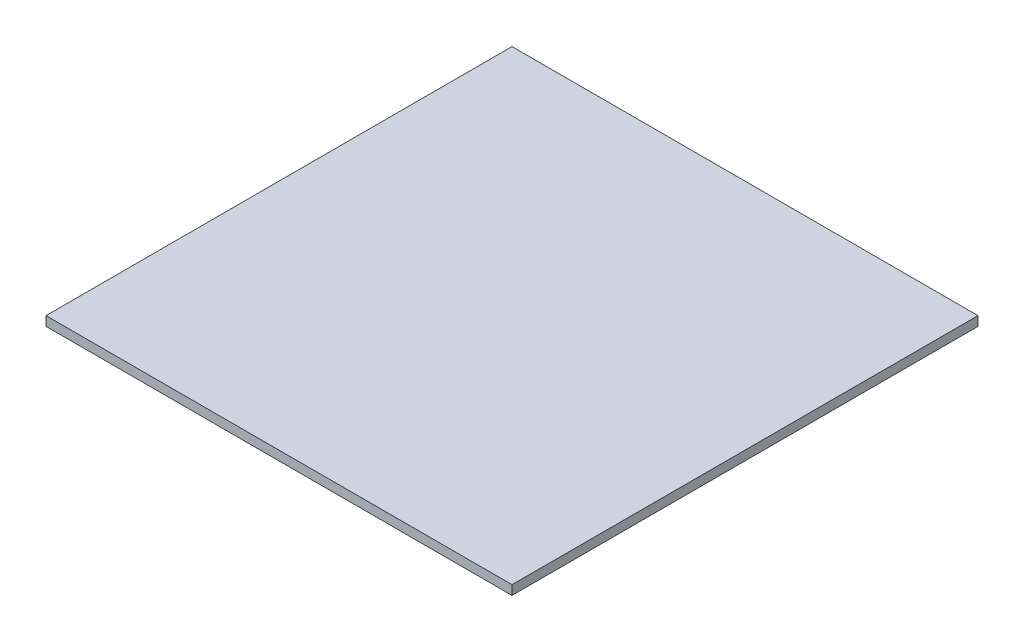
SolidWorks part; units mm, degrees
ref_plane "Přední rovina" through (0, 0, 0) normal (0, 0, 1) x (1, 0, 0)
ref_plane "Horní rovina" through (0, 0, 0) normal (0, 1, 0) x (1, 0, 0)
ref_plane "Pravá rovina" through (0, 0, 0) normal (1, 0, 0) x (0, 0, -1)
sketch "Skica1" plane through (0, 0, 0) normal (0, 1, 0) x (1, 0, 0)
  line L1 (0, 0) -> (127, 0)
  line L2 (0, 0) -> (0, 127)
  line L3 (0, 127) -> (127, 127)
  line L4 (127, 0) -> (127, 127)
  dimension "D1" = 127
  dimension "D2" = 127
extrude "Přidat vysunutím1" add sketch "Skica1" along normal blind 2.54
